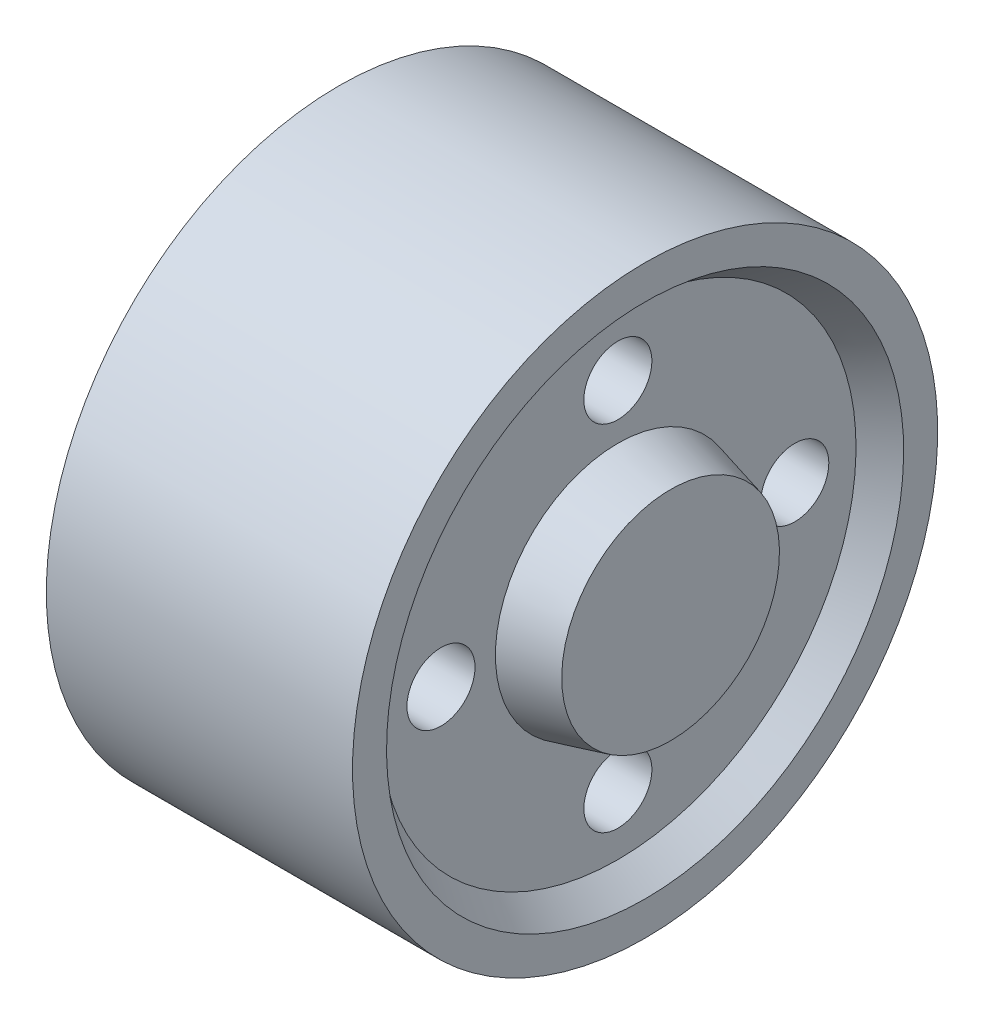
SolidWorks part; units mm, degrees
ref_plane "Front Plane" through (0, 0, 0) normal (0, 0, 1) x (1, 0, 0)
ref_plane "Top Plane" through (0, 0, 0) normal (0, 1, 0) x (1, 0, 0)
ref_plane "Right Plane" through (0, 0, 0) normal (1, 0, 0) x (0, 0, -1)
sketch "Sketch1" plane through (0, 0, 0) normal (0, 0, 1) x (1, 0, 0)
  line L0 (0, 0) -> (0, 48.91) construction
  line L1 (0, 0) -> (0, 16)
  line L2 (0, 16) -> (7.746, 18)
  line L3 (7.746, 18) -> (7.746, 35)
  line L4 (7.746, 35) -> (3.746, 38)
  line L5 (3.746, 38) -> (3.746, 43)
  line L6 (3.746, 43) -> (48.746, 43)
  line L7 (26.246, 50.2796) -> (26.246, 0) construction
  line L8 (0, 0) -> (52.4919, 0) construction
  line L9 (48.746, 38) -> (48.746, 43)
  line L10 (44.746, 35) -> (48.746, 38)
  line L11 (44.746, 18) -> (44.746, 35)
  line L12 (52.4919, 16) -> (44.746, 18)
  line L13 (52.4919, 0) -> (52.4919, 16)
  line L14 (0, 0) -> (52.4919, 0)
  point P12 (25.9336, 42.9953)
  point P14 (26.246, 43)
  dimension "D1" = 16
  dimension "D2" = 18
  dimension "D3" = 35
  dimension "D4" = 38
  dimension "D5" = 8
  dimension "D6" = 5
  dimension "D7" = 22.5
  dimension "D8" = 43
revolve "Revolve1" add sketch "Sketch1" angle 360 about L14
sketch "Sketch2" plane through (52.4919, 0, 0) normal (1, 0, 0) x (0, 0, -1)
  line L0 (0, 0) -> (0, 43) construction
  line L1 (0, 0) -> (0, -43) construction
  line L2 (0, 0) -> (43, 0) construction
  line L3 (0, 0) -> (-43, 0) construction
  line L4 (0, 0) -> (43, 0) construction
  line L5 (0, 0) -> (0, -43) construction
  line L6 (0, 0) -> (-43, 0) construction
  circle A0 centre (0, 0) radius 43 construction
  circle A1 centre (0, 0) radius 26 construction
  circle A2 centre (0, 26) radius 5
  circle A3 centre (26, 0) radius 5
  circle A4 centre (0, -26) radius 5
  circle A5 centre (-26, 0) radius 5
  point P24 (0, 0)
  dimension "D1" = 52
  dimension "D2" = 10
  dimension "D3" = 4
extrude "Cut-Extrude2" cut sketch "Sketch2" against normal blind 50
